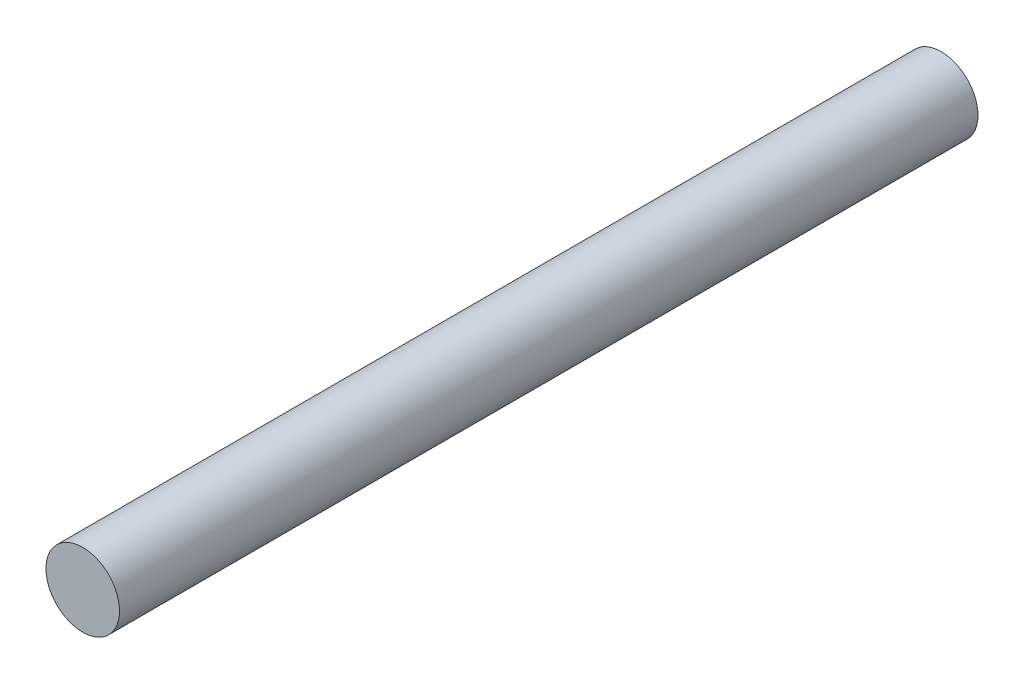
SolidWorks part; units mm, degrees
ref_plane "Front" through (0, 0, 0) normal (0, 0, 1) x (1, 0, 0)
ref_plane "Top" through (0, 0, 0) normal (0, 1, 0) x (1, 0, 0)
ref_plane "Right" through (0, 0, 0) normal (1, 0, 0) x (0, 0, -1)
sketch "Esquisse1" plane through (0, 0, 0) normal (0, 0, 1) x (1, 0, 0)
  circle A0 centre (0, 0) radius 1.5
  dimension "D1" = 3
extrude "Boss.-Extru.1" add sketch "Esquisse1" along normal blind 35
